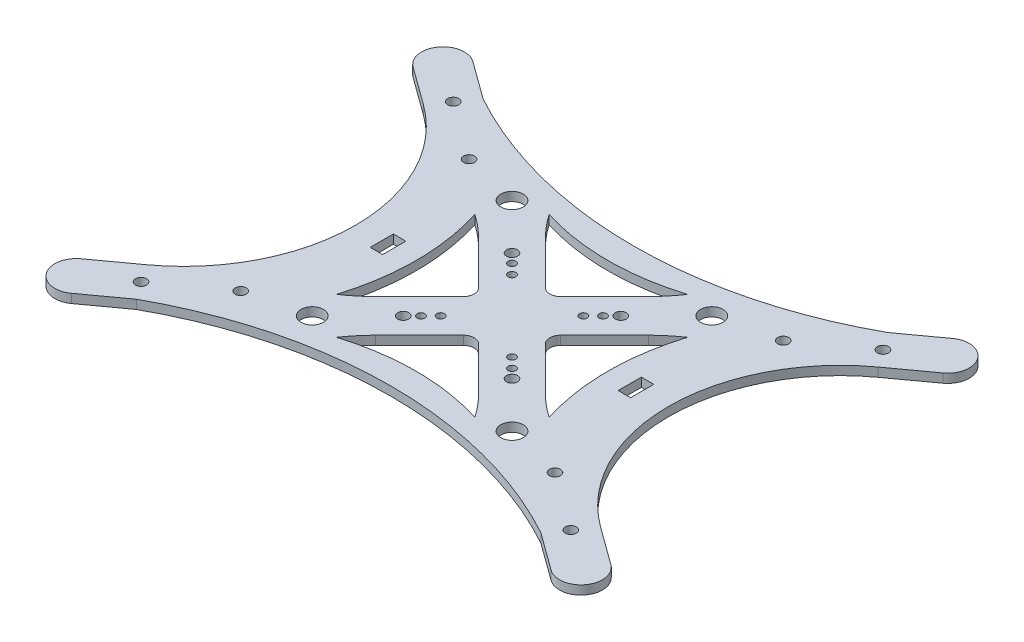
SolidWorks part; units mm, degrees
material "Thornel VCB-20 碳布"
ref_plane "前视基准面" through (0, 0, 0) normal (0, 0, 1) x (1, 0, 0)
ref_plane "上视基准面" through (0, 0, 0) normal (0, 1, 0) x (1, 0, 0)
ref_plane "右视基准面" through (0, 0, 0) normal (1, 0, 0) x (0, 0, -1)
sketch "另一块板" plane through (0, 0, 0) normal (0, 1, 0) x (1, 0, 0)
  line L0 (-126.4995, 0) -> (116.8967, 0) construction
  line L1 (121.619, 121.619) -> (-121.619, -121.619) construction
  line L2 (0, 104.5414) -> (0, -99.6328) construction
  line L3 (-108.3893, 108.3893) -> (124.9236, -124.9236) construction
  line L4 (0, 0) -> (86.3378, -62.728) construction
  line L5 (21.6521, 58.45) -> (28.8521, 58.45)
  line L6 (21.1521, 43.45) -> (21.1521, 57.95)
  line L7 (-10.7467, 23.3214) -> (-10.7467, 21.1638)
  line L8 (-7.6467, 21.1638) -> (-7.6467, 23.3214)
  line L9 (-10.6003, 23.6749) -> (-9.5503, 24.7249)
  line L10 (-8.8432, 24.7249) -> (-7.7932, 23.6749)
  line L11 (-7.7932, 20.8103) -> (-8.8432, 19.7603)
  line L12 (-9.5503, 19.7603) -> (-10.6003, 20.8103)
  line L13 (21.6521, 42.95) -> (28.8521, 42.95)
  line L14 (34.6494, 84.6384) -> (47.6818, 96.1449)
  line L15 (0, 82.79) -> (0, 88.225) construction
  line L16 (17.0991, -107.7737) -> (17.0991, -105.6162)
  line L17 (-25.125, 92.5026) -> (-29.6185, 96.226)
  line L18 (44.1232, 159.0629) -> (28.3883, 151.5629)
  line L19 (27.2573, -98.177) -> (28.7573, -98.177)
  line L20 (35.4016, 59.0549) -> (34.6494, 84.6384)
  line L21 (79.3904, 159.0629) -> (44.1232, 159.0629)
  line L22 (15.9026, -104.2126) -> (16.9526, -105.2626)
  line L23 (14.1455, -105.2626) -> (15.1955, -104.2126)
  line L24 (-16.9545, -108.1273) -> (-15.9045, -109.1773)
  line L25 (79.3904, 144.0629) -> (79.3904, 159.0629)
  line L26 (27.2573, -98.177) -> (27.2573, -63.5957)
  line L27 (67.2151, -56.251) -> (56.6859, -48.6011)
  line L28 (47.6818, 144.0629) -> (79.3904, 144.0629)
  line L29 (74.2685, -46.5428) -> (63.7393, -38.8929)
  line L30 (-15.1974, -109.1773) -> (-14.1474, -108.1273)
  line L31 (-14.0009, -105.6162) -> (-14.0009, -107.7737)
  line L32 (-14.1474, -105.2626) -> (-15.1974, -104.2126)
  line L33 (-47.6818, 96.1449) -> (-47.6818, 144.0629)
  line L34 (-34.6494, 84.6384) -> (-47.6818, 96.1449)
  line L35 (-35.4016, 59.0549) -> (-34.6494, 84.6384)
  line L36 (28.7573, -98.177) -> (28.7573, -103.177)
  line L37 (2.5276, 44.6015) -> (7.8986, 41.6512)
  line L38 (-7.8986, 41.6512) -> (-2.5276, 44.6015)
  line L39 (-1.6288, 25.4456) -> (1.6288, 25.4456)
  line L40 (-5.924, 41.4234) -> (-4.2339, 27.7486)
  line L41 (5.924, 41.4234) -> (4.2339, 27.7486)
  line L42 (-7.8986, 41.6512) -> (-5.924, 41.4234)
  line L43 (7.8986, 41.6512) -> (5.924, 41.4234)
  line L44 (10.6003, 23.6749) -> (9.5503, 24.7249)
  line L45 (0, 72.0242) -> (0, 60.8242) construction
  line L46 (21.1521, 50.7) -> (32.5559, 50.7) construction
  line L47 (25.2521, 58.45) -> (25.2521, 42.95) construction
  line L48 (29.3521, 57.95) -> (29.3521, 43.45)
  line L49 (8.8432, 24.7249) -> (7.7932, 23.6749)
  line L50 (7.6467, 21.1638) -> (7.6467, 23.3214)
  line L51 (-28.3, 64.3716) -> (-2.5276, 64.3716) construction
  line L52 (7.7932, 20.8103) -> (8.8432, 19.7603)
  line L53 (28.7573, -103.177) -> (27.2573, -103.177)
  line L54 (-15.9045, -104.2126) -> (-16.9545, -105.2626)
  line L55 (-17.1009, -107.7737) -> (-17.1009, -105.6162)
  line L56 (4.1009, -56.25) -> (4.1009, -53.2975)
  line L57 (-3.6009, -56.75) -> (3.6009, -56.75)
  line L58 (3.6009, -40.75) -> (-3.5991, -40.75)
  line L59 (4.1009, -41.25) -> (4.1009, -44.2025)
  line L60 (-4.1009, -56.25) -> (-4.1009, -53.2961)
  line L61 (-4.1009, -44.2011) -> (-4.1009, -41.2481)
  line L62 (-4.5484, -52.9461) -> (-4.4509, -52.9461)
  line L63 (-8.5484, -48.9461) -> (-8.5484, -48.5511)
  line L64 (8.5484, -48.9475) -> (8.5484, -48.5525)
  line L65 (4.4509, -52.9475) -> (4.5484, -52.9475)
  line L66 (4.5484, -44.5525) -> (4.4509, -44.5525)
  line L67 (-4.5484, -44.5511) -> (-4.4509, -44.5511)
  line L68 (13.9991, -105.6162) -> (13.9991, -107.7737)
  line L69 (15.1955, -109.1773) -> (14.1455, -108.1273)
  line L70 (16.9526, -108.1273) -> (15.9026, -109.1773)
  line L71 (18.9991, -62.5) -> (18.9991, -100.5) construction
  line L72 (18.9991, -100.5) -> (-19.0009, -100.5) construction
  line L73 (-19.0009, -62.5) -> (-19.0009, -100.5) construction
  line L74 (27.2573, -103.177) -> (27.2573, -111.177)
  line L75 (16.4174, -141.0041) -> (16.4174, -159.5041)
  line L76 (16.4174, -141.0041) -> (12.3174, -141.0041)
  line L77 (12.3174, -141.0041) -> (12.3174, -170.0041)
  line L78 (19.4666, -159.5041) -> (16.4174, -159.5041)
  line L79 (19.4666, -165.5542) -> (19.4666, -159.5041)
  line L80 (-3.8169, -155.5041) -> (-7.6919, -170.0041)
  line L81 (-7.6919, -170.0041) -> (-12.3174, -170.0041)
  line L82 (23.4926, -163.4505) -> (19.4666, -165.5542)
  line L83 (-19.4666, -165.5542) -> (-19.4666, -159.5041)
  line L84 (-19.4666, -159.5041) -> (-16.4174, -159.5041)
  line L85 (-12.3174, -141.0041) -> (-12.3174, -170.0041)
  line L86 (-16.4174, -141.0041) -> (-12.3174, -141.0041)
  line L87 (-16.4174, -141.0041) -> (-16.4174, -159.5041)
  line L88 (7.4592, -170.0041) -> (12.3174, -170.0041)
  line L89 (-3.8169, -155.5041) -> (3.6009, -155.5041)
  line L90 (3.6009, -155.5041) -> (7.4592, -170.0041)
  line L91 (-23.1028, -164.168) -> (-19.4666, -165.5542)
  line L92 (-10.8641, -115.9341) -> (-6.9283, -109.8213)
  line L93 (-10.5808, -123.7337) -> (-5.8541, -129.2069)
  line L94 (-5.8541, -129.2069) -> (5.8541, -129.2069)
  line L95 (-11.4015, -121.5278) -> (-11.4015, -117.7612)
  line L96 (27.2573, -111.177) -> (28.7573, -111.177)
  line L97 (28.2798, -130.7335) -> (28.2798, -154.6401)
  line L98 (28.2798, -154.6401) -> (23.4926, -163.4505)
  line L99 (-28.2798, -154.6401) -> (-23.1028, -164.168)
  line L100 (-28.2798, -130.7335) -> (-28.2798, -154.6401)
  line L101 (28.7573, -111.177) -> (28.7573, -116.177)
  line L102 (28.7573, -116.177) -> (27.2573, -116.177)
  line L103 (27.2573, -116.177) -> (27.2573, -129.3732)
  line L104 (27.2573, -129.3732) -> (28.2798, -130.7335)
  line L105 (-27.2573, -98.177) -> (-27.2573, -63.5957)
  line L106 (-27.2573, -129.3732) -> (-28.2798, -130.7335)
  line L107 (-27.2573, -116.177) -> (-27.2573, -129.3732)
  line L108 (-28.7573, -116.177) -> (-27.2573, -116.177)
  line L109 (-28.7573, -111.177) -> (-28.7573, -116.177)
  line L110 (-27.2573, -111.177) -> (-28.7573, -111.177)
  line L111 (-27.2573, -103.177) -> (-27.2573, -111.177)
  line L112 (-28.7573, -103.177) -> (-27.2573, -103.177)
  line L113 (-28.7573, -98.177) -> (-28.7573, -103.177)
  line L114 (-27.2573, -98.177) -> (-28.7573, -98.177)
  line L115 (-67.2151, 56.251) -> (-56.6859, 48.6011)
  line L116 (-74.2685, 46.5428) -> (-63.7393, 38.8929)
  line L117 (-74.2685, -46.5428) -> (-63.7393, -38.8929)
  line L118 (-67.2151, -56.251) -> (-56.6859, -48.6011)
  line L119 (-47.6818, 144.0629) -> (-79.3904, 144.0629)
  line L120 (-79.3904, 144.0629) -> (-79.3904, 159.0629)
  line L121 (-79.3904, 159.0629) -> (-44.1232, 159.0629)
  line L122 (-44.1232, 159.0629) -> (-28.3883, 151.5629)
  line L123 (47.6818, 96.1449) -> (47.6818, 144.0629)
  line L124 (0, -114.8485) -> (0, -146.3095) construction
  line L125 (-5.6802, -109.2069) -> (5.6802, -109.2069)
  line L126 (10.5808, -123.7337) -> (5.8541, -129.2069)
  line L127 (11.4015, -121.5278) -> (11.4015, -117.7612)
  line L128 (10.8641, -115.9341) -> (6.9283, -109.8213)
  line L129 (-19.0009, -62.5) -> (18.9991, -62.5) construction
  line L130 (9.5503, 19.7603) -> (10.6003, 20.8103)
  line L131 (10.7467, 23.3214) -> (10.7467, 21.1638)
  line L132 (-11.2799, 76.5216) -> (-6.2799, 76.5216) construction
  line L133 (-11.2799, 77.8216) -> (-6.2799, 77.8216)
  line L134 (-11.2799, 75.2216) -> (-6.2799, 75.2216)
  line L135 (-11.2799, 52.2216) -> (-6.2799, 52.2216) construction
  line L136 (-11.2799, 50.9216) -> (-6.2799, 50.9216)
  line L137 (-11.2799, 53.5216) -> (-6.2799, 53.5216)
  line L138 (5.7201, 76.5216) -> (0.7201, 76.5216) construction
  line L139 (5.7201, 75.2216) -> (0.7201, 75.2216)
  line L140 (5.7201, 77.8216) -> (0.7201, 77.8216)
  line L141 (5.7201, 52.2216) -> (0.7201, 52.2216) construction
  line L142 (5.7201, 53.5216) -> (0.7201, 53.5216)
  line L143 (5.7201, 50.9216) -> (0.7201, 50.9216)
  line L144 (74.2685, 46.5428) -> (63.7393, 38.8929)
  line L145 (44.0442, 32) -> (60.2246, 43.7557) construction
  line L146 (67.2151, 56.251) -> (56.6859, 48.6011)
  line L147 (25.125, 92.5026) -> (29.6185, 96.226)
  circle A0 centre (10, 10) radius 1.075
  circle A1 centre (12.75, 12.75) radius 1.075
  circle A2 centre (15.25, 15.25) radius 1.55
  circle A3 centre (-15.25, 15.25) radius 1.55
  circle A4 centre (-12.75, 12.75) radius 1.075
  circle A5 centre (-10, 10) radius 1.075
  circle A6 centre (-10, -10) radius 1.075
  circle A7 centre (-12.75, -12.75) radius 1.075
  circle A8 centre (-15.25, -15.25) radius 1.55
  circle A9 centre (15.25, -15.25) radius 1.55
  circle A10 centre (12.75, -12.75) radius 1.075
  circle A11 centre (10, -10) radius 1.075
  circle A12 centre (28, -28) radius 3.15
  circle A13 centre (-28, -28) radius 3.15
  circle A14 centre (25.2521, 60.9) radius 1.05
  arc A15 (21.1521, 57.95) -> (21.6521, 58.45) centre (21.1521, 58.45) cw
  arc A16 (21.1521, 43.45) -> (21.6521, 42.95) centre (21.1521, 42.95) ccw
  arc A17 (-8.8432, 19.7603) -> (-9.5503, 19.7603) centre (-9.1967, 20.1138) cw
  arc A18 (-10.7467, 21.1638) -> (-10.6003, 20.8103) centre (-10.2467, 21.1638) ccw
  arc A19 (-7.6467, 21.1638) -> (-7.7932, 20.8103) centre (-8.1467, 21.1638) cw
  arc A20 (-7.6467, 23.3214) -> (-7.7932, 23.6749) centre (-8.1467, 23.3214) ccw
  arc A21 (-10.7467, 23.3214) -> (-10.6003, 23.6749) centre (-10.2467, 23.3214) cw
  arc A22 (-9.5503, 24.7249) -> (-8.8432, 24.7249) centre (-9.1967, 24.3714) cw
  circle A23 centre (25.2521, 40.5) radius 1.05
  circle A24 centre (17.238, 84.7633) radius 2.75
  circle A25 centre (-17.238, 84.7633) radius 2.75
  circle A26 centre (-39.335, 104.0823) radius 2.75
  circle A27 centre (-39.335, 129.0823) radius 2.75
  circle A28 centre (-28, 28) radius 3.15
  circle A29 centre (28, 28) radius 3.15
  circle A30 centre (63.4501, 151.5629) radius 1.55
  circle A31 centre (44.0442, -32) radius 1.55
  circle A32 centre (60.2246, -43.7557) radius 1.55
  circle A33 centre (-60.2246, -43.7557) radius 1.55
  arc A34 (2.5276, 44.6015) -> (-2.5276, 44.6015) centre (0, 40) ccw
  arc A35 (1.6288, 25.4456) -> (4.2339, 27.7486) centre (1.6288, 28.0706) ccw
  arc A36 (-1.6288, 25.4456) -> (-4.2339, 27.7486) centre (-1.6288, 28.0706) cw
  arc A37 (29.3521, 57.95) -> (28.8521, 58.45) centre (29.3521, 58.45) ccw
  arc A38 (29.3521, 43.45) -> (28.8521, 42.95) centre (29.3521, 42.95) cw
  circle A39 centre (-23.2799, 76.5216) radius 1.3
  circle A40 centre (-23.2799, 52.2216) radius 1.3
  circle A41 centre (-44.0442, -32) radius 1.55
  circle A42 centre (60.2246, 43.7557) radius 1.55
  circle A43 centre (44.0442, 32) radius 1.55
  circle A44 centre (-44.0442, 32) radius 1.55
  circle A45 centre (-60.2246, 43.7557) radius 1.55
  arc A46 (-11.2799, 77.8216) -> (-11.2799, 75.2216) centre (-11.2799, 76.5216) ccw
  arc A47 (67.2151, -56.251) -> (74.2685, -46.5428) centre (70.7418, -51.3969) ccw
  arc A48 (27.2573, -63.5957) -> (56.6859, -48.6011) centre (45.7917, -63.5957) cw
  arc A49 (-17.1009, -107.7737) -> (-16.9545, -108.1273) centre (-16.6009, -107.7737) ccw
  arc A50 (-15.9045, -109.1773) -> (-15.1974, -109.1773) centre (-15.5509, -108.8237) ccw
  arc A51 (-14.0009, -107.7737) -> (-14.1474, -108.1273) centre (-14.5009, -107.7737) cw
  arc A52 (-14.0009, -105.6162) -> (-14.1474, -105.2626) centre (-14.5009, -105.6162) ccw
  arc A53 (-15.1974, -104.2126) -> (-15.9045, -104.2126) centre (-15.5509, -104.5662) ccw
  arc A54 (-17.1009, -105.6162) -> (-16.9545, -105.2626) centre (-16.6009, -105.6162) cw
  arc A55 (-4.1009, -56.25) -> (-3.6009, -56.75) centre (-4.1009, -56.75) ccw
  arc A56 (4.1009, -56.25) -> (3.6009, -56.75) centre (4.1009, -56.75) cw
  arc A57 (4.1009, -41.25) -> (3.6009, -40.75) centre (4.1009, -40.75) ccw
  arc A58 (-4.1009, -41.2481) -> (-3.5991, -40.75) centre (-4.0991, -40.7481) cw
  arc A59 (8.5484, -48.5525) -> (4.5484, -44.5525) centre (4.5484, -48.5525) ccw
  arc A60 (-4.5484, -44.5511) -> (-8.5484, -48.5511) centre (-4.5484, -48.5511) ccw
  arc A61 (-4.5484, -52.9461) -> (-8.5484, -48.9461) centre (-4.5484, -48.9461) cw
  arc A62 (8.5484, -48.9475) -> (4.5484, -52.9475) centre (4.5484, -48.9475) cw
  arc A63 (4.1009, -44.2025) -> (4.4509, -44.5525) centre (4.4509, -44.2025) ccw
  arc A64 (4.1009, -53.2975) -> (4.4509, -52.9475) centre (4.4509, -53.2975) cw
  arc A65 (-4.1009, -44.2011) -> (-4.4509, -44.5511) centre (-4.4509, -44.2011) cw
  arc A66 (-4.1009, -53.2961) -> (-4.4509, -52.9461) centre (-4.4509, -53.2961) ccw
  arc A67 (17.0991, -107.7737) -> (16.9526, -108.1273) centre (16.5991, -107.7737) cw
  arc A68 (17.0991, -105.6162) -> (16.9526, -105.2626) centre (16.5991, -105.6162) ccw
  arc A69 (15.1955, -104.2126) -> (15.9026, -104.2126) centre (15.5491, -104.5662) cw
  arc A70 (13.9991, -105.6162) -> (14.1455, -105.2626) centre (14.4991, -105.6162) cw
  arc A71 (13.9991, -107.7737) -> (14.1455, -108.1273) centre (14.4991, -107.7737) ccw
  arc A72 (15.9026, -109.1773) -> (15.1955, -109.1773) centre (15.5491, -108.8237) cw
  circle A73 centre (-22.3899, -133.8062) radius 1.55
  circle A74 centre (22.3899, -133.8062) radius 1.55
  circle A75 centre (-16.9009, -98.4) radius 1.55
  circle A76 centre (16.8991, -98.4) radius 1.55
  arc A77 (-5.6802, -109.2069) -> (-6.9283, -109.8213) centre (-5.7932, -110.5521) ccw
  arc A78 (-11.4015, -117.7612) -> (-10.8641, -115.9341) centre (-8.0265, -117.7612) cw
  arc A79 (-10.5808, -123.7337) -> (-11.4015, -121.5278) centre (-8.0265, -121.5278) cw
  circle A80 centre (-14.6009, -133.8062) radius 1.55
  circle A81 centre (14.6009, -133.8062) radius 1.55
  arc A82 (10.5808, -123.7337) -> (11.4015, -121.5278) centre (8.0265, -121.5278) ccw
  arc A83 (11.4015, -117.7612) -> (10.8641, -115.9341) centre (8.0265, -117.7612) ccw
  arc A84 (5.6802, -109.2069) -> (6.9283, -109.8213) centre (5.7932, -110.5521) cw
  arc A85 (10.7467, 23.3214) -> (10.6003, 23.6749) centre (10.2467, 23.3214) ccw
  arc A86 (9.5503, 24.7249) -> (8.8432, 24.7249) centre (9.1967, 24.3714) ccw
  arc A87 (7.6467, 23.3214) -> (7.7932, 23.6749) centre (8.1467, 23.3214) cw
  arc A88 (7.6467, 21.1638) -> (7.7932, 20.8103) centre (8.1467, 21.1638) ccw
  arc A89 (8.8432, 19.7603) -> (9.5503, 19.7603) centre (9.1967, 20.1138) ccw
  arc A90 (10.7467, 21.1638) -> (10.6003, 20.8103) centre (10.2467, 21.1638) cw
  arc A91 (-6.2799, 75.2216) -> (-6.2799, 77.8216) centre (-6.2799, 76.5216) ccw
  arc A92 (-11.2799, 50.9216) -> (-11.2799, 53.5216) centre (-11.2799, 52.2216) cw
  arc A93 (-6.2799, 53.5216) -> (-6.2799, 50.9216) centre (-6.2799, 52.2216) cw
  arc A94 (5.7201, 75.2216) -> (5.7201, 77.8216) centre (5.7201, 76.5216) ccw
  arc A95 (0.7201, 77.8216) -> (0.7201, 75.2216) centre (0.7201, 76.5216) ccw
  arc A96 (5.7201, 53.5216) -> (5.7201, 50.9216) centre (5.7201, 52.2216) cw
  arc A97 (0.7201, 50.9216) -> (0.7201, 53.5216) centre (0.7201, 52.2216) cw
  arc A98 (-28.3883, 151.5629) -> (-29.6185, 96.226) centre (122.812, 120.5195) ccw
  arc A99 (28.3883, 151.5629) -> (29.6185, 96.226) centre (-122.812, 120.5195) cw
  circle A100 centre (-16.9009, -65.108) radius 1.55
  circle A101 centre (16.9009, -65.108) radius 1.55
  circle A102 centre (0, -38.5) radius 1.55
  circle A103 centre (0, -59) radius 1.55
  arc A104 (67.2151, 56.251) -> (74.2685, 46.5428) centre (70.7418, 51.3969) cw
  arc A105 (63.7393, 38.8929) -> (63.7393, -38.8929) centre (91.9966, 0) ccw
  circle A106 centre (44.0442, -32) radius 6 construction
  arc A107 (35.4016, 59.0549) -> (56.6859, 48.6011) centre (48.8045, 59.4489) ccw
  arc A108 (-67.2151, 56.251) -> (-74.2685, 46.5428) centre (-70.7418, 51.3969) ccw
  arc A109 (-35.4016, 59.0549) -> (-56.6859, 48.6011) centre (-48.8045, 59.4489) cw
  arc A110 (-63.7393, 38.8929) -> (-63.7393, -38.8929) centre (-91.9966, 0) cw
  arc A111 (-67.2151, -56.251) -> (-74.2685, -46.5428) centre (-70.7418, -51.3969) cw
  arc A112 (-27.2573, -63.5957) -> (-56.6859, -48.6011) centre (-45.7917, -63.5957) ccw
  circle A113 centre (-63.4501, 151.5629) radius 1.55
  circle A114 centre (39.335, 129.0823) radius 2.75
  circle A115 centre (39.335, 104.0823) radius 2.75
  arc A116 (-25.125, 92.5026) -> (25.125, 92.5026) centre (0, 215.2587) ccw
  point P45 (-8.7799, 76.5216)
  point P107 (3.2201, 76.5216)
  point P112 (-8.7799, 52.2216)
  point P168 (3.2201, 52.2216)
  point P346 (0, -129.2069)
  point P353 (7.3036, -118.1341)
  point P356 (0, -109.2069)
  dimension "D1" = 2.15
  dimension "D4" = 3.1
  dimension "D7" = 0.5
  dimension "D11" = 2.6
  dimension "D13" = 3.1
  dimension "D32" = 3.1
  dimension "D34" = 3.1
  dimension "D37" = 12
  dimension "D40" = 12
  dimension "D45" = 3.1
  dimension "D2" = 10
  dimension "D3" = 2.75
  dimension "D5" = 2.5
  dimension "D6" = 36
  dimension "D8" = 15.5
  dimension "D9" = 2.45
  dimension "D10" = 8.2
  dimension "D12" = 25
  dimension "D14" = 32
  dimension "D15" = 2.1
  dimension "D16" = 10.5
  dimension "D17" = 14.5
  dimension "D18" = 4
  dimension "D19" = 4.1
  dimension "D20" = 20
  dimension "D21" = 40.75
  dimension "D22" = 7.2
  dimension "D23" = 16
  dimension "D24" = 62.5
  dimension "D25" = 38
  dimension "D26" = 7.2
  dimension "D27" = 24.3
  dimension "D28" = 50.7
  dimension "D29" = 12
  dimension "D30" = 5
  dimension "D31" = 12
  dimension "D33" = 2.608
  dimension "D35" = 2.25
  dimension "D36" = 2.25
  dimension "D38" = 13
  dimension "D39" = 20
  dimension "D41" = 5
  dimension "D42" = 1.5
  dimension "D43" = 8
  dimension "D44" = 15
  dimension "D46" = 7.5
  dimension "D47" = 40
sketch "草图1" plane through (0, 0, 0) normal (0, 1, 0) x (1, 0, 0)
  line L0 (-137.4469, 0) -> (193.7386, 0) construction
  line L1 (0, 90.5001) -> (0, -188.7446) construction
  line L2 (0, 0) -> (86.3378, -62.728) construction
  line L48 (74.2685, -46.5428) -> (63.7393, -38.8929)
  line L61 (-44.0442, 32) -> (-60.2246, 43.7557) construction
  line L62 (0, 0) -> (-86.3378, -62.728) construction
  line L66 (-67.2151, 56.251) -> (-56.6859, 48.6011)
  line L82 (-74.2685, 46.5428) -> (-63.7393, 38.8929)
  line L93 (74.2685, 46.5428) -> (63.7393, 38.8929)
  line L94 (44.0442, 32) -> (60.2246, 43.7557) construction
  line L95 (67.2151, 56.251) -> (56.6859, 48.6011)
  line L101 (-74.2685, -46.5428) -> (-63.7393, -38.8929)
  line L102 (-67.2151, -56.251) -> (-56.6859, -48.6011)
  line L103 (67.2151, -56.251) -> (56.6859, -48.6011)
  circle A40 centre (10, 10) radius 1.075
  circle A65 centre (12.75, 12.75) radius 1.075
  circle A66 centre (15.25, 15.25) radius 1.55
  circle A73 centre (15.25, -15.25) radius 1.55
  circle A74 centre (12.75, -12.75) radius 1.075
  circle A75 centre (10, -10) radius 1.075
  circle A76 centre (28, -28) radius 3.15
  circle A89 centre (28, 28) radius 3.15
  circle A90 centre (44.0442, -32) radius 1.55
  circle A91 centre (60.2246, -43.7557) radius 1.55
  circle A100 centre (60.2246, 43.7557) radius 1.55
  circle A101 centre (44.0442, 32) radius 1.55
  arc A104 (67.2151, -56.251) -> (74.2685, -46.5428) centre (70.7418, -51.3969) ccw
  arc A132 (67.2151, 56.251) -> (74.2685, 46.5428) centre (70.7418, 51.3969) cw
  arc A133 (63.7393, 38.8929) -> (63.7393, -38.8929) centre (91.9966, 0) ccw
  circle A134 centre (44.0442, -32) radius 6 construction
  arc A135 (-56.6859, -48.6011) -> (56.6859, -48.6011) centre (0, -151.3241) cw
  circle A136 centre (-44.0442, -32) radius 6 construction
  arc A138 (-63.7393, 38.8929) -> (-63.7393, -38.8929) centre (-91.9966, 0) cw
  arc A139 (-67.2151, 56.251) -> (-74.2685, 46.5428) centre (-70.7418, 51.3969) ccw
  arc A147 (-67.2151, -56.251) -> (-74.2685, -46.5428) centre (-70.7418, -51.3969) cw
  circle A148 centre (-44.0442, 32) radius 1.55
  circle A149 centre (-60.2246, 43.7557) radius 1.55
  circle A150 centre (-60.2246, -43.7557) radius 1.55
  circle A151 centre (-44.0442, -32) radius 1.55
  circle A152 centre (-28, 28) radius 3.15
  circle A153 centre (-28, -28) radius 3.15
  circle A154 centre (-10, -10) radius 1.075
  circle A155 centre (-12.75, -12.75) radius 1.075
  circle A156 centre (-15.25, -15.25) radius 1.55
  circle A157 centre (-15.25, 15.25) radius 1.55
  circle A158 centre (-12.75, 12.75) radius 1.075
  circle A159 centre (-10, 10) radius 1.075
  arc A160 (-27.2573, -63.5957) -> (-56.6859, -48.6011) centre (-45.7917, -63.5957) ccw construction
  arc A166 (-56.6859, 48.6011) -> (56.6859, 48.6011) centre (0, 151.3241) ccw
  point P38 (0, 0)
  dimension "D2" = 2.75
  dimension "D4" = 2.5
  dimension "D13" = 13
  dimension "D14" = 20
  dimension "D15" = 12
  dimension "D1" = 2.15
  dimension "D3" = 3.1
  dimension "D6" = 3.1
  dimension "D5" = 6
  dimension "D7" = 36
  dimension "D16" = 36
extrude "凸台-拉伸1" add sketch "草图1" along normal blind 2.5
sketch "草图2" plane through (0, 2.5, 0) normal (0, 1, 0) x (1, 0, 0)
  line L3 (-23.8014, 14.4296) -> (-9.3719, 0)
  line L9 (-58.8867, 0) -> (57.6096, 0) construction
  line L14 (-23.8014, -14.4296) -> (-9.3719, 0)
  line L15 (0, 29.8455) -> (0, -115.5328) construction
  line L29 (14.4296, 23.8014) -> (0, 9.3719)
  line L30 (-14.4296, 23.8014) -> (0, 9.3719)
  line L31 (23.8014, -14.4296) -> (9.3719, 0)
  line L32 (23.8014, 14.4296) -> (9.3719, 0)
  line L33 (-14.4296, -23.8014) -> (0, -9.3719)
  line L34 (14.4296, -23.8014) -> (0, -9.3719)
  arc A18 (-23.8014, 14.4296) -> (-29.8202, 19.4008) centre (-52.8883, -14.6573) ccw
  arc A19 (-23.8014, -14.4296) -> (-29.8202, -19.4008) centre (-52.8883, 14.6573) cw
  arc A20 (-29.8202, -19.4008) -> (-29.8202, 19.4008) centre (-91.9966, 0) ccw
  arc A33 (-14.4296, 23.8014) -> (-19.4008, 29.8202) centre (14.6573, 52.8883) cw
  arc A34 (-19.4008, 29.8202) -> (19.4008, 29.8202) centre (0, 91.9966) ccw
  arc A35 (14.4296, 23.8014) -> (19.4008, 29.8202) centre (-14.6573, 52.8883) ccw
  arc A36 (23.8014, 14.4296) -> (29.8202, 19.4008) centre (52.8883, -14.6573) cw
  arc A37 (29.8202, 19.4008) -> (29.8202, -19.4008) centre (91.9966, 0) ccw
  arc A38 (23.8014, -14.4296) -> (29.8202, -19.4008) centre (52.8883, 14.6573) ccw
  arc A39 (14.4296, -23.8014) -> (19.4008, -29.8202) centre (-14.6573, -52.8883) cw
  arc A40 (19.4008, -29.8202) -> (-19.4008, -29.8202) centre (0, -91.9966) ccw
  arc A41 (-14.4296, -23.8014) -> (-19.4008, -29.8202) centre (14.6573, -52.8883) ccw
  point P49 (0, 0)
  dimension "D1" = 4
extrude "切除-拉伸1" cut sketch "草图2" against normal up to next
fillet "圆角1" radius 3 4 edges at (-9.3719, 1.25, 0) (0, 1.25, 9.3719) (9.3719, 1.25, 0) (0, 1.25, -9.3719)
sketch "草图4" plane through (0, 2.5, 0) normal (0, 1, 0) x (1, 0, 0)
  line L0 (-96.7808, 0) -> (86.8563, 0) construction
  line L1 (0, 52.226) -> (0, -62.4511) construction
  line L2 (36.5, -3.25) -> (33, -3.25)
  line L3 (-36.5, 3.25) -> (-33, 3.25)
  line L4 (-36.5, 3.25) -> (-36.5, -3.25)
  line L5 (-36.5, -3.25) -> (-33, -3.25)
  line L6 (-33, 3.25) -> (-33, -3.25)
  line L7 (33, 3.25) -> (33, -3.25)
  line L8 (36.5, 3.25) -> (33, 3.25)
  line L9 (36.5, 3.25) -> (36.5, -3.25)
  dimension "D1" = 33
  dimension "D2" = 6.5
  dimension "D3" = 3.5
extrude "切除-拉伸2" cut sketch "草图4" against normal up to next
